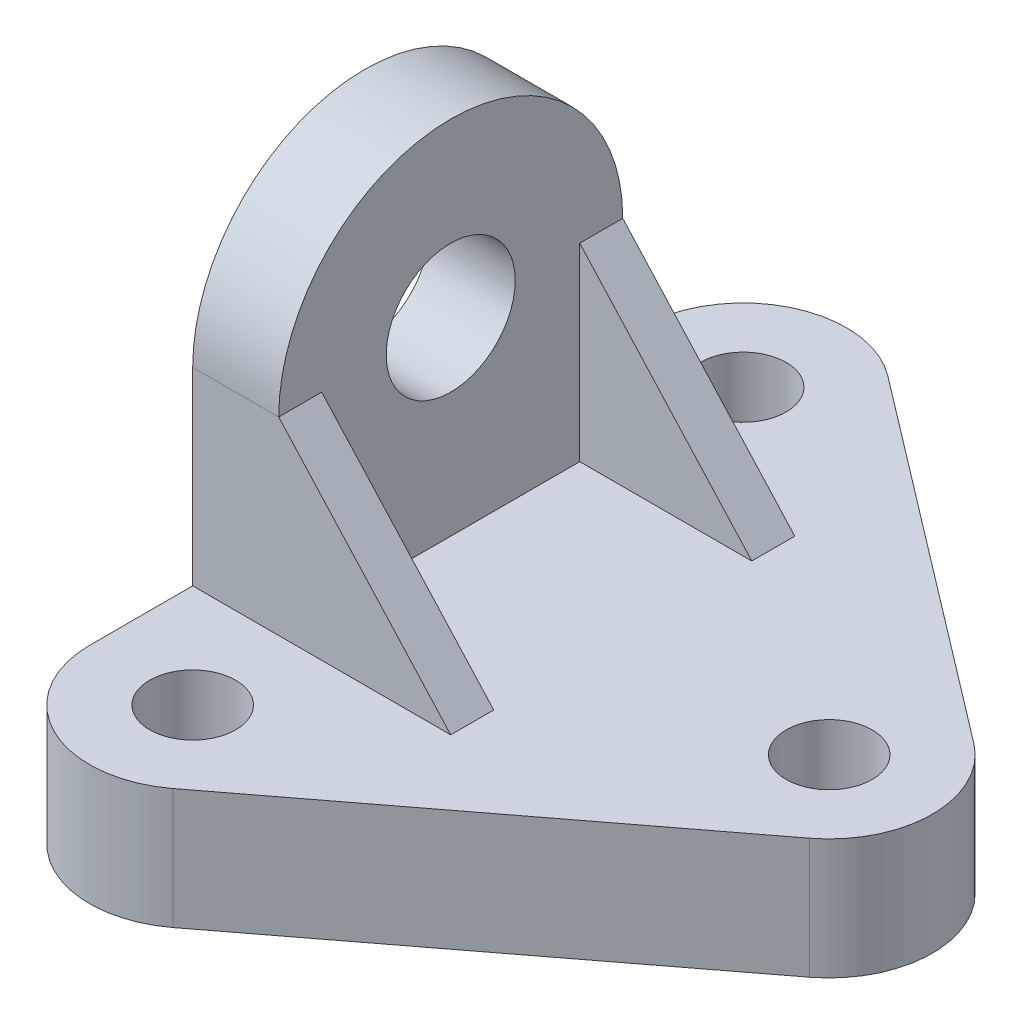
SolidWorks part; units mm, degrees
ref_plane "Front Plane" through (0, 0, 0) normal (0, 0, 1) x (1, 0, 0)
ref_plane "Top Plane" through (0, 0, 0) normal (0, 1, 0) x (1, 0, 0)
ref_plane "Right Plane" through (0, 0, 0) normal (1, 0, 0) x (0, 0, -1)
sketch "Sketch1" plane through (0, 0, 0) normal (0, 1, 0) x (1, 0, 0)
  line L0 (-55, 0) -> (55, 0) construction
  line L1 (-54, 32) -> (-54, -32)
  line L2 (-34.7275, 41.5452) -> (7.2725, 9.5452)
  line L3 (-34.7275, -41.5452) -> (7.2725, -9.5452)
  arc A0 (7.2725, -9.5452) -> (7.2725, 9.5452) centre (0, 0) ccw
  arc A1 (-34.7275, 41.5452) -> (-54, 32) centre (-42, 32) ccw
  arc A2 (-34.7275, -41.5452) -> (-54, -32) centre (-42, -32) cw
  circle A3 centre (-42, 32) radius 5
  circle A4 centre (0, 0) radius 5
  circle A5 centre (-42, -32) radius 5
  dimension "D1" = 24
  dimension "D2" = 24
  dimension "D5" = 10
  dimension "D3" = 42
  dimension "D4" = 32
extrude "Boss-Extrude1" add sketch "Sketch1" along normal blind 14
sketch "Sketch2" plane through (0, 14, 0) normal (0, 1, 0) x (1, 0, 0)
  line L0 (0, 0) -> (-68.2371, 0) construction
  line L1 (-54, 32) -> (-54, -32) construction
  line L2 (-54, 20) -> (-44, 20)
  line L3 (-54, 20) -> (-54, -20)
  line L4 (-54, -20) -> (-44, -20)
  line L5 (-44, 20) -> (-44, -20)
  dimension "D1" = 40
  dimension "D2" = 10
extrude "Boss-Extrude2" add sketch "Sketch2" along normal blind 22
sketch "Sketch4" plane through (-54, 0, 0) normal (-1, 0, 0) x (0, 0, 1)
  line L0 (-20, 36) -> (20, 36) construction
  line L1 (20, 36) -> (20, 14) construction
  circle A0 centre (0, 36) radius 20
extrude "Boss-Extrude3" add sketch "Sketch4" against normal up to surface (10 mm away) up to face at (-44, 25, 0)
hole_wizard "Hole1" positions "Sketch5" profile "Sketch6" legacy end condition through all
sketch "Sketch5" plane through (-44, 0, 0) normal (1, 0, 0) x (0, 0, -1)
  point P0 (0, 36)
sketch "Sketch6" plane through (-44, 36, 0) normal (0, 1, 0) x (0, 0, -1)
  line L0 (0, 0) -> (0, 10)
  line L1 (0, 10) -> (7.5, 10)
  line L2 (7.5, 10) -> (7.5, 0)
  line L3 (7.5, 0) -> (0, 0)
  line L4 (0, 110) -> (0, -10) construction
  dimension "Diameter" = 15
  dimension "Depth" = 10
sketch "Sketch7" plane through (0, 0, 20) normal (0, 0, 1) x (1, 0, 0)
  line L0 (-44, 36) -> (-24, 14)
  line L1 (-34.7275, 14) -> (7.2725, 14) construction
  line L2 (-24, 14) -> (-44, 14)
  line L3 (-44, 14) -> (-44, 36)
  dimension "D1" = 20
extrude "Boss-Extrude4" add sketch "Sketch7" against normal blind 5
sketch "Sketch8" plane through (0, 0, -20) normal (0, 0, -1) x (-1, 0, 0)
  line L0 (44, 36) -> (44, 14) construction
  line L1 (44, 14) -> (24, 14) construction
  line L2 (24, 14) -> (44, 36) construction
  line L3 (44, 36) -> (44, 14)
  line L4 (44, 14) -> (24, 14)
  line L5 (24, 14) -> (44, 36)
extrude "Boss-Extrude5" add sketch "Sketch8" against normal blind 5
